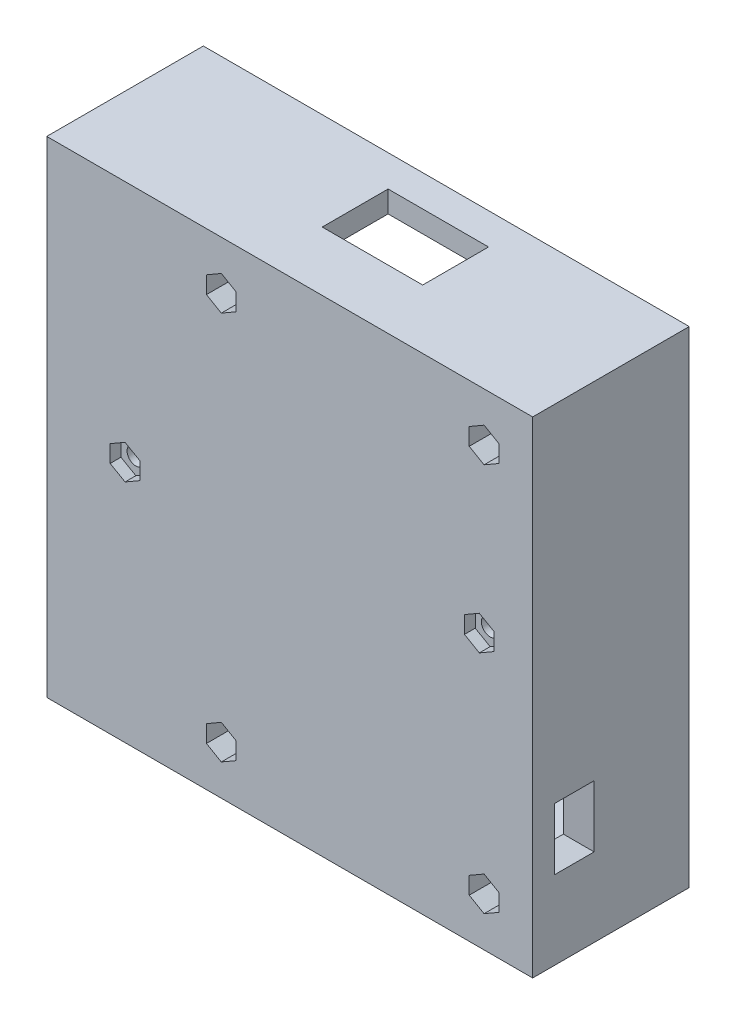
SolidWorks part; units mm, degrees
ref_plane "Alzado" through (0, 0, 0) normal (0, 0, 1) x (1, 0, 0)
ref_plane "Planta" through (0, 0, 0) normal (0, 1, 0) x (1, 0, 0)
ref_plane "Vista lateral" through (0, 0, 0) normal (1, 0, 0) x (0, 0, -1)
sketch "Croquis1" plane through (0, 0, 0) normal (0, 0, 1) x (1, 0, 0)
  line L0 (-44.4885, -46.7117) -> (45.5115, -46.7117)
  line L1 (45.5115, -46.7117) -> (45.5115, 43.2883)
  line L2 (34.2095, -31.6555) -> (34.2095, -33.0328) construction
  line L4 (-43.9885, 43.2883) -> (-45.9617, 43.2883) construction
  line L5 (-44.4885, 42.7883) -> (-44.4885, 44.5722) construction
  line L6 (-44.4885, 43.2883) -> (-44.4885, -46.7117)
  line L7 (-44.4885, 43.2883) -> (45.5115, 43.2883)
  dimension "D1" = 34.2095
  dimension "D2" = 45.5115
extrude "Saliente-Extruir1" add sketch "Croquis1" along normal blind 4
sketch "Croquis2" plane through (0, 0, 0) normal (0, 0, -1) x (-1, 0, 0)
  line L0 (-19.2301, 43.2883) -> (-19.2301, 39.2883) construction
  line L1 (-45.5115, 43.2883) -> (44.4885, 43.2883) construction
  line L2 (-45.5115, 28.7784) -> (-41.5115, 28.7784) construction
  line L3 (-45.5115, -46.7117) -> (-45.5115, 43.2883) construction
  line L4 (-24.9283, -46.7117) -> (-24.9283, -42.7117) construction
  line L5 (44.4885, -46.7117) -> (-45.5115, -46.7117) construction
  line L6 (44.4885, -27.1574) -> (40.4885, -27.1574) construction
  line L7 (44.4885, 43.2883) -> (44.4885, -46.7117) construction
  line L8 (40.4885, -27.1574) -> (40.4885, -42.7117)
  line L9 (40.4885, -42.7117) -> (-41.5115, -42.7117)
  line L10 (-41.5115, -42.7117) -> (-41.5115, 39.2883)
  line L11 (-41.5115, 39.2883) -> (40.4885, 39.2883)
  line L12 (40.4885, 39.2883) -> (40.4885, -27.1574)
  line L14 (-45.5115, 43.2883) -> (44.4885, 43.2883)
  line L15 (-45.5115, 43.2883) -> (-45.5115, -46.7117)
  line L16 (-45.5115, -46.7117) -> (44.4885, -46.7117)
  line L17 (44.4885, 43.2883) -> (44.4885, -46.7117)
  dimension "D1" = 4
  dimension "D2" = 20.5832
  dimension "D3" = 26.2813
  dimension "D4" = 19.5543
  dimension "D5" = 75.4901
extrude "Saliente-Extruir2" add sketch "Croquis2" along normal blind 25
sketch "Croquis4" plane through (45.5115, 0, 0) normal (1, 0, 0) x (0, 0, -1)
  line L0 (2.411, -26.4653) -> (-4, -26.4653) construction
  line L1 (0, -21.4747) -> (0, -31.4518)
  line L5 (0, -31.4518) -> (0, -32.1752)
  line L6 (0, -32.1752) -> (7.3834, -32.1752)
  line L13 (7.3834, -32.1752) -> (7.3834, -31.4518)
  line L14 (-4, -25.6688) -> (0, -25.6688) construction
  line L15 (7.3834, -21.4747) -> (7.3834, -20.7513)
  line L16 (7.3834, -21.4747) -> (7.3834, -31.4518)
  line L18 (7.3834, -20.7513) -> (0, -20.7513)
  line L19 (0, -20.7513) -> (0, -21.4747)
extrude "Cortar-Extruir1" cut sketch "Croquis4" against normal blind 4 draft 23
sketch "Croquis6" plane through (0, 0, 0) normal (0, 0, -1) x (-1, 0, 0)
  line L0 (-41.5115, 39.2883) -> (-41.5115, -42.7117) construction
  line L1 (-41.5115, 39.2883) -> (-31.5115, 39.2883)
  line L2 (-41.5115, 39.2883) -> (-41.5115, 29.2883)
  line L3 (-41.5115, 29.2883) -> (-31.5115, 29.2883)
  line L4 (-31.5115, 39.2883) -> (-31.5115, 29.2883)
  line L5 (40.4885, 39.2883) -> (-41.5115, 39.2883) construction
  line L6 (-41.5115, -42.7117) -> (40.4885, -42.7117) construction
  line L7 (-41.5115, -42.7117) -> (-31.5115, -42.7117)
  line L8 (-41.5115, -42.7117) -> (-41.5115, -32.7117)
  line L9 (-41.5115, -32.7117) -> (-31.5115, -32.7117)
  line L10 (-31.5115, -42.7117) -> (-31.5115, -32.7117)
  line L11 (-41.5115, 39.2883) -> (-41.5115, -42.7117) construction
  line L12 (40.4885, 39.2883) -> (-41.5115, 39.2883) construction
  line L14 (17.1571, -42.7117) -> (7.1571, -42.7117)
  line L15 (17.1571, -42.7117) -> (17.1571, -32.7117)
  line L16 (17.1571, -32.7117) -> (7.1571, -32.7117)
  line L17 (7.1571, -42.7117) -> (7.1571, -32.7117)
  line L18 (17.1571, 39.2883) -> (7.1571, 39.2883)
  line L19 (17.1571, 39.2883) -> (17.1571, 29.2883)
  line L20 (17.1571, 29.2883) -> (7.1571, 29.2883)
  line L21 (7.1571, 39.2883) -> (7.1571, 29.2883)
  dimension "D1" = 10
  dimension "D2" = 48.6686
extrude "Saliente-Extruir4" add sketch "Croquis6" along normal blind 4
sketch "Croquis7" plane through (0, 0, -4) normal (0, 0, -1) x (-1, 0, 0)
  line L0 (-36.5115, -32.7117) -> (-36.5115, -42.7117) construction
  line L1 (-31.5115, -32.7117) -> (-41.5115, -32.7117) construction
  line L2 (-41.5115, -42.7117) -> (40.4885, -42.7117) construction
  line L3 (-36.5115, 29.2883) -> (-36.5115, 39.2883) construction
  line L4 (-41.5115, 29.2883) -> (-31.5115, 29.2883) construction
  line L5 (40.4885, 39.2883) -> (-41.5115, 39.2883) construction
  line L6 (-31.5115, 34.2883) -> (-41.5115, 34.2883) construction
  line L7 (-31.5115, 29.2883) -> (-31.5115, 39.2883) construction
  line L8 (-41.5115, 39.2883) -> (-41.5115, -42.7117) construction
  line L9 (-31.5115, -37.7117) -> (-41.5115, -37.7117) construction
  line L10 (-31.5115, -42.7117) -> (-31.5115, -32.7117) construction
  line L12 (12.1571, -32.7117) -> (12.1571, -42.7117) construction
  line L13 (17.1571, -32.7117) -> (7.1571, -32.7117) construction
  line L14 (12.1571, 29.2883) -> (12.1571, 39.2883) construction
  line L15 (7.1571, 29.2883) -> (17.1571, 29.2883) construction
  line L16 (-41.5115, 39.2883) -> (-41.5115, 29.2883) construction
  circle A0 centre (-36.5115, 34.2883) radius 1.625
  circle A1 centre (-36.5115, -37.7117) radius 1.625
  circle A2 centre (12.1571, -37.7117) radius 1.625
  circle A3 centre (12.1571, 34.2883) radius 1.625
  dimension "D1" = 3.25
extrude "Cortar-Extruir2" cut sketch "Croquis7" against normal up to vertex
sketch "Croquis8" plane through (0, 0, 4) normal (0, 0, 1) x (1, 0, 0)
  line L0 (45.5115, -46.7117) -> (45.5115, 43.2883) construction
  line L1 (36.5115, -40.8917) -> (39.2654, -39.3017)
  line L2 (39.2654, -39.3017) -> (39.2654, -36.1217)
  line L3 (39.2654, -36.1217) -> (36.5115, -34.5317)
  line L4 (36.5115, -34.5317) -> (33.7575, -36.1217)
  line L5 (33.7575, -36.1217) -> (33.7575, -39.3017)
  line L6 (33.7575, -39.3017) -> (36.5115, -40.8917)
  line L7 (36.5115, 31.1083) -> (39.2654, 32.6983)
  line L8 (39.2654, 32.6983) -> (39.2654, 35.8783)
  line L9 (39.2654, 35.8783) -> (36.5115, 37.4683)
  line L10 (36.5115, 37.4683) -> (33.7575, 35.8783)
  line L11 (33.7575, 35.8783) -> (33.7575, 32.6983)
  line L12 (33.7575, 32.6983) -> (36.5115, 31.1083)
  circle A0 centre (36.5115, -37.7117) radius 2.754 construction
  circle A1 centre (36.5115, 34.2883) radius 2.754 construction
  dimension "D1" = 5.5079
  dimension "D2" = 6.246
  dimension "D3" = 5.82
  dimension "D4" = 77.82
extrude "Cortar-Extruir3" cut sketch "Croquis8" against normal blind 6
sketch "Croquis9" plane through (0, 0, 0) normal (0, 0, -1) x (-1, 0, 0)
  line L0 (40.4885, -42.7117) -> (40.4885, 39.2883) construction
  line L1 (-31.5115, -42.7117) -> (7.1571, -42.7117) construction
  circle A0 centre (-35.6315, 3.6783) radius 1.625
  circle A1 centre (29.9885, -1.7117) radius 1.625
  dimension "D1" = 3.25
  dimension "D2" = 10.5
  dimension "D3" = 76.12
  dimension "D4" = 41
  dimension "D5" = 46.39
extrude "Cortar-Extruir4" cut sketch "Croquis9" against normal up to vertex (4 mm away)
sketch "Croquis10" plane through (0, 0, 4) normal (0, 0, 1) x (1, 0, 0)
  line L0 (39.2654, -39.3017) -> (39.2654, -36.1217) construction
  line L1 (-29.9885, -4.8917) -> (-27.2346, -3.3017)
  line L2 (-27.2346, -3.3017) -> (-27.2346, -0.1217)
  line L3 (-27.2346, -0.1217) -> (-29.9885, 1.4683)
  line L4 (-29.9885, 1.4683) -> (-32.7425, -0.1217)
  line L5 (-32.7425, -0.1217) -> (-32.7425, -3.3017)
  line L6 (-32.7425, -3.3017) -> (-29.9885, -4.8917)
  line L7 (35.6315, 0.4983) -> (38.3854, 2.0883)
  line L8 (38.3854, 2.0883) -> (38.3854, 5.2683)
  line L9 (38.3854, 5.2683) -> (35.6315, 6.8583)
  line L10 (35.6315, 6.8583) -> (32.8775, 5.2683)
  line L11 (32.8775, 5.2683) -> (32.8775, 2.0883)
  line L12 (32.8775, 2.0883) -> (35.6315, 0.4983)
  circle A0 centre (-29.9885, -1.7117) radius 2.754 construction
  circle A1 centre (35.6315, 3.6783) radius 2.754 construction
  dimension "D1" = 5.5079
  dimension "D2" = 0.88
  dimension "D3" = 66.5
  dimension "D4" = 36
  dimension "D5" = 41.39
extrude "Cortar-Extruir5" cut sketch "Croquis10" against normal blind 2
sketch "Croquis11" plane through (0, 0, 4) normal (0, 0, 1) x (1, 0, 0)
  line L0 (-32.7425, -0.1217) -> (-32.7425, -3.3017) construction
  line L1 (-12.1571, 31.1083) -> (-9.4031, 32.6983)
  line L2 (-9.4031, 32.6983) -> (-9.4031, 35.8783)
  line L3 (-9.4031, 35.8783) -> (-12.1571, 37.4683)
  line L4 (-12.1571, 37.4683) -> (-14.9111, 35.8783)
  line L5 (-14.9111, 35.8783) -> (-14.9111, 32.6983)
  line L6 (-14.9111, 32.6983) -> (-12.1571, 31.1083)
  line L7 (-12.1571, -34.5317) -> (-14.9111, -36.1217)
  line L8 (-14.9111, -36.1217) -> (-14.9111, -39.3017)
  line L9 (-14.9111, -39.3017) -> (-12.1571, -40.8917)
  line L10 (-12.1571, -40.8917) -> (-9.4031, -39.3017)
  line L11 (-9.4031, -39.3017) -> (-9.4031, -36.1217)
  line L12 (-9.4031, -36.1217) -> (-12.1571, -34.5317)
  circle A0 centre (-12.1571, 34.2883) radius 2.754 construction
  circle A1 centre (-12.1571, -37.7117) radius 2.754 construction
  dimension "D1" = 5.5079
  dimension "D2" = 17.8314
  dimension "D3" = 72
extrude "Cortar-Extruir6" cut sketch "Croquis11" against normal blind 6
sketch "Croquis14" plane through (0, 43.2883, 0) normal (0, 1, 0) x (1, 0, 0)
  line L1 (-4.4359, 19.1737) -> (14.1641, 19.1737)
  line L2 (-4.4359, 19.1737) -> (-4.4359, 6.9737)
  line L3 (-4.4359, 6.9737) -> (14.1641, 6.9737)
  line L4 (14.1641, 19.1737) -> (14.1641, 6.9737)
  line L6 (45.5115, -4) -> (45.5115, 25) construction
  line L7 (-44.4885, 25) -> (45.5115, 25) construction
  dimension "D1" = 31.3473
  dimension "D2" = 49.9473
  dimension "D3" = 5.8263
  dimension "D4" = 18.0263
extrude "Cortar-Extruir7" cut sketch "Croquis14" against normal up to vertex (4 mm away)
